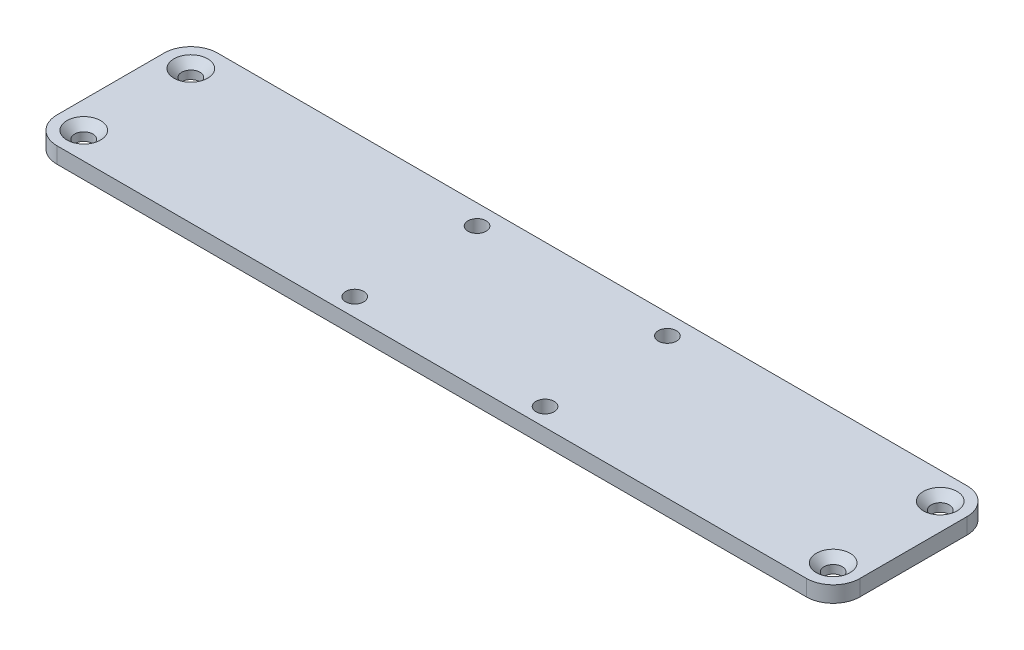
SolidWorks part; units mm, degrees
material "PVC rigido"
ref_plane "Piano frontale" through (0, 0, 0) normal (0, 0, 1) x (1, 0, 0)
ref_plane "Piano superiore" through (0, 0, 0) normal (0, 1, 0) x (1, 0, 0)
ref_plane "Piano destro" through (0, 0, 0) normal (1, 0, 0) x (0, 0, -1)
sketch "Schizzo1" plane through (0, 0, 0) normal (0, 1, 0) x (1, 0, 0)
  line L1 (75, -15) -> (-75, -15)
  line L2 (75, -15) -> (75, 15)
  line L3 (75, 15) -> (-75, 15)
  line L4 (-75, -15) -> (-75, 15)
  line L5 (75, -15) -> (-75, 15) construction
  line L6 (75, 15) -> (-75, -15) construction
  point P0 (0, 0)
  dimension "D1" = 150
  dimension "D2" = 30
extrude "Estrusione-Estrusione1" add sketch "Schizzo1" along normal blind 3
sketch "Schizzo4" plane through (0, 0, 15) normal (0, 0, 1) x (1, 0, 0)
  line L0 (-75, 0) -> (75, 0) construction
  line L1 (45, 0) -> (15, 0)
  line L2 (45, 0) -> (45, 3)
  line L3 (45, 3) -> (15, 3)
  line L4 (15, 0) -> (15, 3)
  line L5 (-75, 3) -> (75, 3) construction
  line L6 (-75, 0) -> (75, 0) construction
  line L7 (-15, 0) -> (-45, 0)
  line L8 (-15, 0) -> (-15, 3)
  line L9 (-15, 3) -> (-45, 3)
  line L10 (-45, 0) -> (-45, 3)
  line L11 (-75, 3) -> (75, 3) construction
  line L12 (15, 1.5) -> (0, 1.5) construction
  line L13 (0, 1.5) -> (-15, 1.5) construction
  line L14 (0, 0) -> (0, 1.5) construction
  dimension "D1" = 30
  dimension "D2" = 15
extrude "Estrusione-Estrusione2" [suppressed] add sketch "Schizzo4" along normal blind 25
hole_wizard "Foro svasato per Vite M3-1" positions "Schizzo3" profile "Schizzo2" countersink size "M3" standard "Ansi Metric" end condition through all
sketch "Schizzo3" plane through (0, 3, 0) normal (0, 1, 0) x (1, 0, 0)
  line L0 (-70, 10) -> (70, 10) construction
  line L1 (70, 10) -> (70, -10) construction
  line L2 (70, -10) -> (-70, -10) construction
  line L3 (-70, -10) -> (-70, 10) construction
  line L5 (-70, 10) -> (70, -10) construction
  line L7 (-70, 0) -> (-75, 0) construction
  line L8 (-75, 15) -> (-75, -15) construction
  line L10 (0, 10) -> (0, 15) construction
  line L11 (75, 15) -> (-75, 15) construction
  point P0 (-70, 10)
  point P2 (-70, -10)
  point P4 (70, -10)
  point P6 (70, 10)
  dimension "D1" = 5
sketch "Schizzo2" plane through (-70, 3, -10) normal (1, 0, 0) x (0, 0, 1)
  line L0 (0, 0) -> (0, 3)
  line L1 (0, 3) -> (1.7, 3)
  line L2 (1.7, 3) -> (1.7, 1.45)
  line L3 (1.7, 1.45) -> (3.15, 0)
  line L5 (3.15, 0) -> (0, 0)
  line L6 (-1.7, 1.45) -> (-3.15, 0) construction
  line L11 (0, -6.35) -> (0, 107.95) construction
  dimension "Thru Hole Dia." = 3.4
  dimension "Thru Hole Depth" = 3
  dimension "Near C'Sink Dia." = 6.3
  dimension "Near C'Sink Angle" = 90
fillet "Raccordo1" radius 5 4 edges at (-75, 1.5, -15) (75, 1.5, -15) (75, 1.5, 15) (-75, 1.5, 15)
hole_wizard "Foro per Vite M3-1" positions "Schizzo6" profile "Schizzo5" hole size "M3" standard "Ansi Metric" end condition through all
sketch "Schizzo6" plane through (0, 3, 0) normal (0, 1, 0) x (1, 0, 0)
  line L0 (17.78, -11.607) -> (-17.78, -11.607) construction
  line L1 (-17.78, -11.607) -> (-17.78, 11.253) construction
  line L2 (-17.78, 11.253) -> (17.78, 11.253) construction
  line L3 (17.78, 11.253) -> (17.78, -11.607) construction
  line L4 (17.78, -11.607) -> (-17.78, 11.253) construction
  line L6 (0, -15) -> (0, -0.177) construction
  line L7 (-70, -15) -> (70, -15) construction
  point P0 (17.78, -11.607)
  point P2 (-17.78, -11.607)
  point P4 (-17.78, 11.253)
  point P6 (17.78, 11.253)
sketch "Schizzo5" plane through (17.78, 3, 11.607) normal (1, 0, 0) x (0, 0, 1)
  line L0 (0, 0) -> (0, 3)
  line L1 (0, 3) -> (1.7, 3)
  line L2 (1.7, 3) -> (1.7, 0)
  line L5 (1.7, 0) -> (0, 0)
  line L11 (0, -6.35) -> (0, 107.95) construction
  dimension "Thru Hole Dia." = 3.4
  dimension "Thru Hole Depth" = 3
